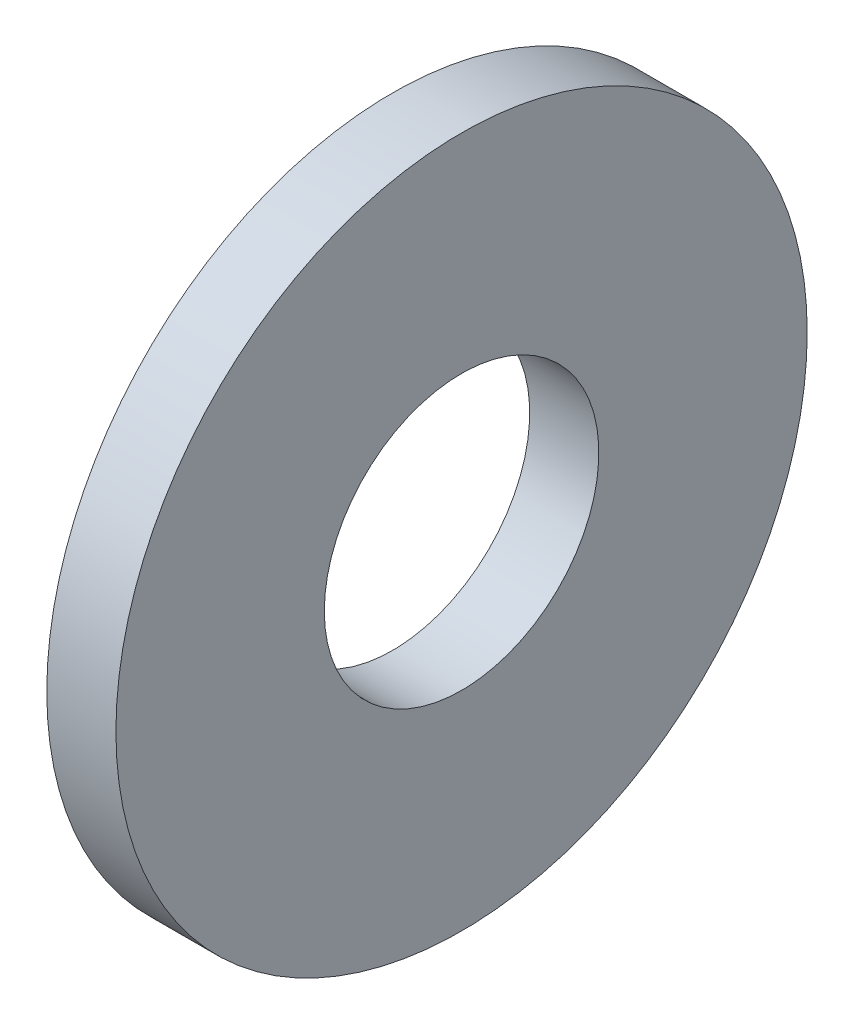
SolidWorks part; units mm, degrees
ref_plane "Plane1" through (0, 0, 0) normal (0, 0, 1) x (1, 0, 0)
ref_plane "Plane2" through (0, 0, 0) normal (0, 1, 0) x (1, 0, 0)
ref_plane "Plane3" through (0, 0, 0) normal (1, 0, 0) x (0, 0, -1)
other "Configuration Table"
sketch "Sketch1" plane through (0, 0, 0) normal (0, 0, 1) x (1, 0, 0)
  line L0 (-34.925, 0) -> (9.525, 0) construction
  line L1 (0, 5.56) -> (0, 14)
  line L2 (0, 14) -> (-2.8, 14)
  line L3 (-2.8, 14) -> (-2.8, 5.56)
  line L4 (-2.8, 5.56) -> (0, 5.56)
  dimension "Thickness" = 2.8
  dimension "Inside_dia" = 11.12
  dimension "Outside_dia" = 28
revolve "Base-Revolve" add sketch "Sketch1" angle 360 about L0
